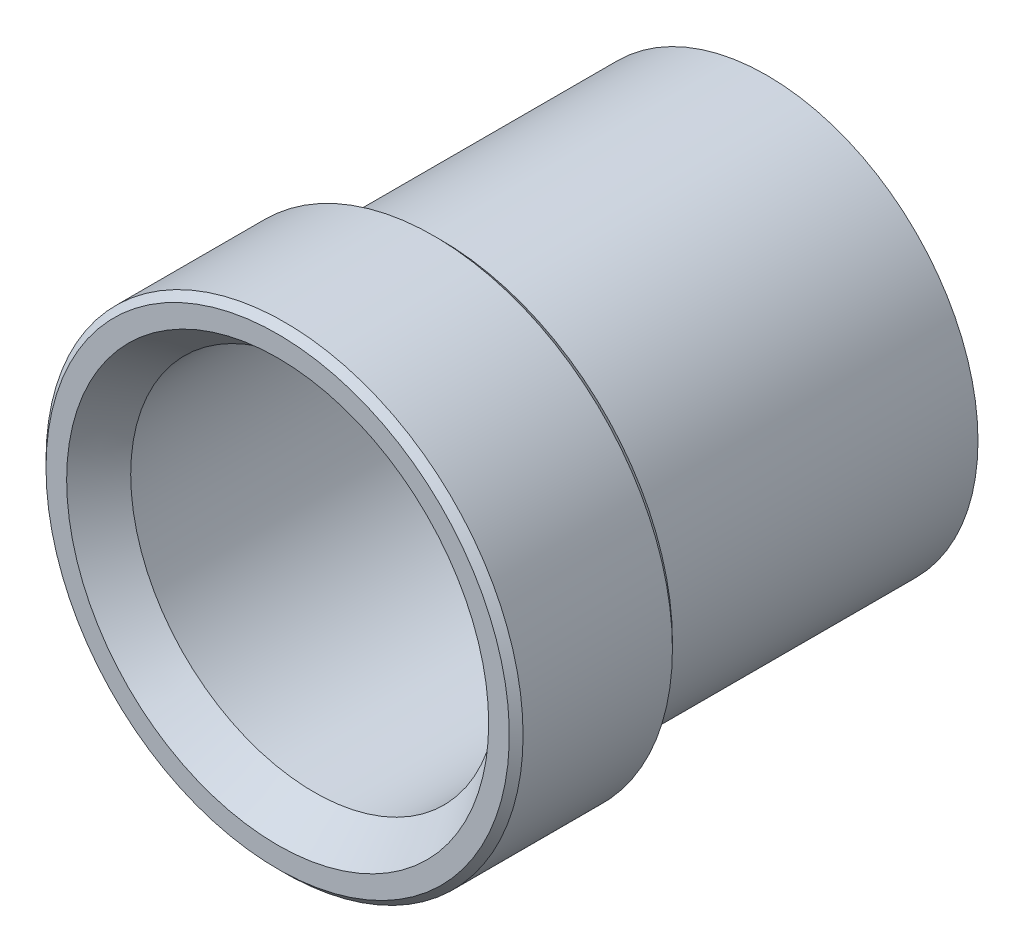
SolidWorks part; units mm, degrees
material "AISI 304"
ref_plane "Front Plane" through (0, 0, 0) normal (0, 0, 1) x (1, 0, 0)
ref_plane "Top Plane" through (0, 0, 0) normal (0, 1, 0) x (1, 0, 0)
ref_plane "Right Plane" through (0, 0, 0) normal (1, 0, 0) x (0, 0, -1)
sketch "Sketch1" plane through (0, 0, 0) normal (1, 0, 0) x (0, 0, -1)
  line L0 (-6.35, 0) -> (6.35, 0) construction
  line L1 (-6.35, 5.4769) -> (-6.35, 6.1913) construction
  line L2 (-6.35, 6.1913) -> (-2.1167, 6.1913) construction
  line L3 (-2.1167, 6.1913) -> (-2.1167, 5.4769) construction
  line L4 (-2.1167, 5.4769) -> (6.35, 5.4769) construction
  line L5 (6.35, 5.4769) -> (6.35, 4.7625) construction
  line L6 (6.35, 4.7625) -> (-5.402, 4.7625) construction
  line L7 (-5.402, 4.7625) -> (-6.35, 5.4769) construction
  dimension "Flared Angle" = 37
  dimension "Length" = 12.7
  dimension "Base Length" = 4.2333
  dimension "Thread Inner Diameter" = 12.3825
  dimension "For Tube OD" = 9.525
sketch "Sketch2" plane through (0, 0, 0) normal (1, 0, 0) x (0, 0, -1)
  line L0 (-5.402, 4.7625) -> (-6.35, 5.4769)
  line L1 (-6.35, 5.4769) -> (-6.35, 6.1913)
  line L2 (-6.35, 6.1913) -> (-2.1167, 6.1913)
  line L3 (-2.1167, 6.1913) -> (-2.1167, 5.4769)
  line L4 (-2.1167, 5.4769) -> (6.35, 5.4769)
  line L5 (6.35, 5.4769) -> (6.35, 4.7625)
  line L6 (6.35, 4.7625) -> (-5.402, 4.7625)
revolve "Revolve1" add sketch "Sketch2" angle 360 about L0
chamfer "Chamfer1" distance 0.1786 angle 45 2 edges at (6.1913, 0, 6.35) (6.1913, 0, 2.1167)
equation "\"D1@Chamfer1\"=(\"Thread Inner Diameter@Sketch1\"-\"For Tube OD@Sketch1\")/16"
equation "\"Base Length@Sketch1\"=\"Length@Sketch1\"/3"
equation "\"Thread Inner Diameter@Sketch1\"=\"For Tube OD@Sketch1\"*1.3"
